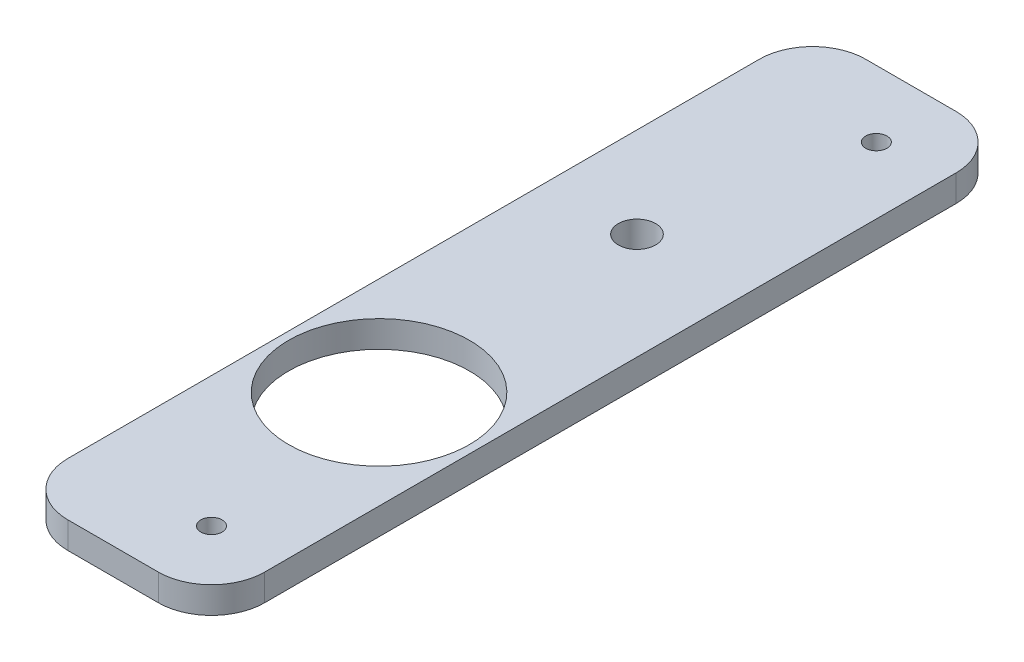
SolidWorks part; units mm, degrees
ref_plane "Alzado" through (0, 0, 0) normal (0, 0, 1) x (1, 0, 0)
ref_plane "Planta" through (0, 0, 0) normal (0, 1, 0) x (1, 0, 0)
ref_plane "Vista lateral" through (0, 0, 0) normal (1, 0, 0) x (0, 0, -1)
sketch "Croquis1" plane through (0, 0, 0) normal (0, 1, 0) x (1, 0, 0)
  line L1 (-18.5, 75) -> (18.5, 75)
  line L2 (-18.5, 75) -> (-18.5, -75)
  line L3 (-18.5, -75) -> (18.5, -75)
  line L4 (18.5, 75) -> (18.5, -75)
  line L5 (-18.5, 75) -> (18.5, -75) construction
  line L6 (-18.5, -75) -> (18.5, 75) construction
  circle A0 centre (-1.5, 25) radius 3.5
  circle A1 centre (0, -25) radius 17
  point P0 (0, 0)
  point P10 (0, 0)
  point P12 (-28.7184, 47.9732)
  dimension "D3" = 50
  dimension "D4" = 50
  dimension "D5" = 7
  dimension "D6" = 34
  dimension "D7" = 20
  dimension "D8" = 18.5
  dimension "D1" = 37
  dimension "D2" = 50
extrude "Saliente-Extruir1" add sketch "Croquis1" along normal blind 5
fillet "Redondeo1" radius 10 4 edges at (18.5, 2.5, -75) (-18.5, 2.5, -75) (18.5, 2.5, 75) (-18.5, 2.5, 75)
sketch "Croquis2" plane through (0, 5, 0) normal (0, 1, 0) x (1, 0, 0)
  line L0 (8.5, 75) -> (-8.5, 75) construction
  line L1 (18.5, -65) -> (18.5, 65) construction
  line L4 (0, 0) -> (18.827, 0) construction
  circle A0 centre (6, 62.5) radius 2
  circle A3 centre (6, -62.5) radius 2
  dimension "D1" = 12.5
  dimension "D2" = 12.5
  dimension "D3" = 4
  dimension "D4" = 12.5
extrude "Cortar-Extruir2" cut sketch "Croquis2" against normal blind 10
